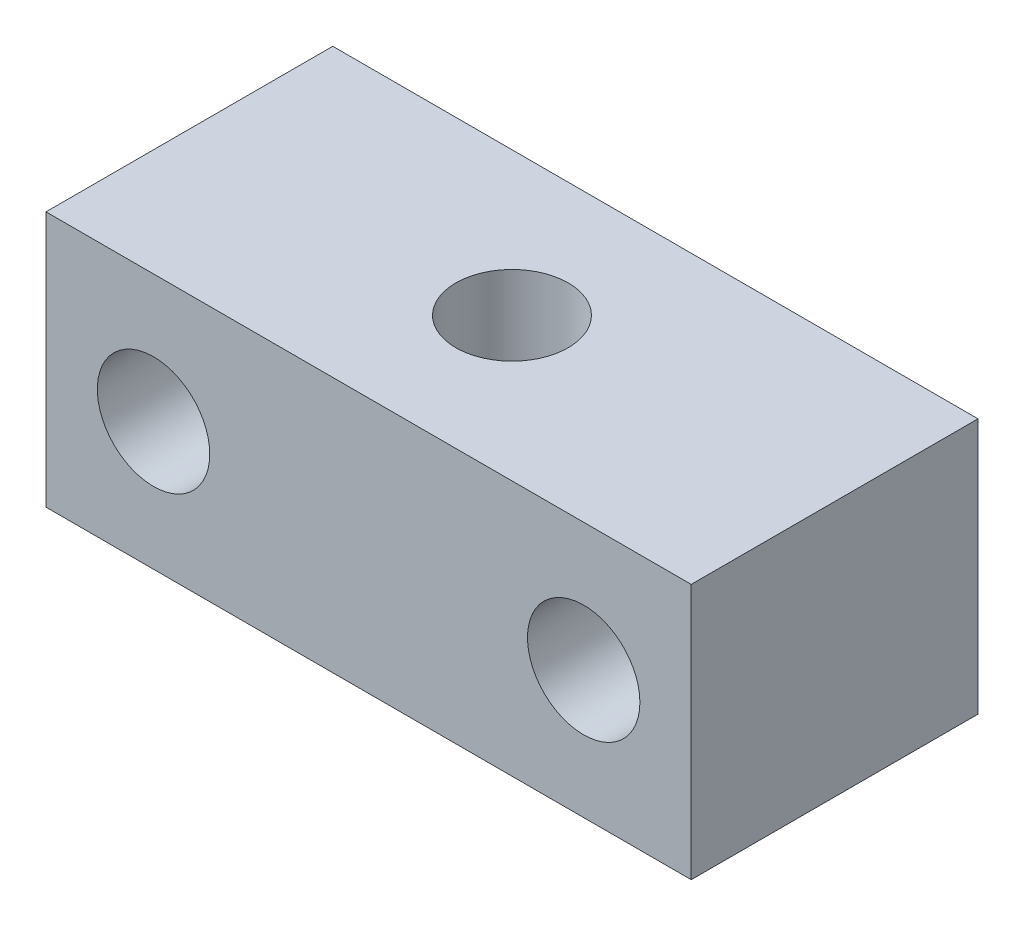
SolidWorks part; units mm, degrees
material "6061-T6 (SS)"
ref_plane "Front Plane" through (0, 0, 0) normal (0, 0, 1) x (1, 0, 0)
ref_plane "Top Plane" through (0, 0, 0) normal (0, 1, 0) x (1, 0, 0)
ref_plane "Right Plane" through (0, 0, 0) normal (1, 0, 0) x (0, 0, -1)
sketch "Sketch1" plane through (0, 0, 0) normal (0, 0, 1) x (1, 0, 0)
  line L0 (-9.525, 0) -> (9.525, 0) construction
  line L1 (-9.525, -5.6642) -> (9.525, -5.6642)
  line L2 (-9.525, 5.6642) -> (9.525, 5.6642)
  line L4 (-9.525, -5.6642) -> (-14.2875, -5.6642)
  line L6 (-9.525, 5.6642) -> (-14.2875, 5.6642)
  line L7 (-14.2875, -5.6642) -> (-14.2875, 5.6642)
  line L8 (9.525, -5.6642) -> (14.2875, -5.6642)
  line L10 (9.525, 5.6642) -> (14.2875, 5.6642)
  line L11 (14.2875, -5.6642) -> (14.2875, 5.6642)
  circle A0 centre (-9.525, 0) radius 2.4892
  circle A1 centre (9.525, 0) radius 2.4892
  point P4 (0, 0)
  point P14 (14.2875, 0)
  dimension "D2" = 4.9784
  dimension "D3" = 11.3284
  dimension "D4" = 4.7625
  dimension "D5" = 4.7625
  dimension "D1" = 19.05
extrude "Boss-Extrude1" add sketch "Sketch1" along normal mid plane 12.7
sketch "Sketch3" plane through (0, 5.6642, 0) normal (0, 1, 0) x (1, 0, 0)
  circle A0 centre (0, 0) radius 2.4892
  dimension "D1" = 4.9784
extrude "Cut-Extrude1" cut sketch "Sketch3" against normal through all
